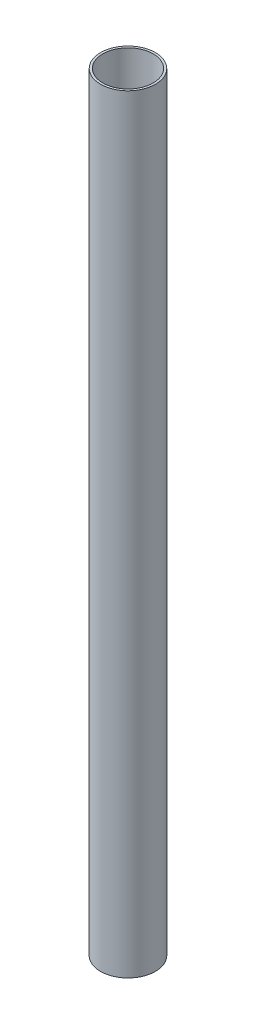
SolidWorks part; units mm, degrees
ref_plane "Front Plane" through (0, 0, 0) normal (0, 0, 1) x (1, 0, 0)
ref_plane "Top Plane" through (0, 0, 0) normal (0, 1, 0) x (1, 0, 0)
ref_plane "Right Plane" through (0, 0, 0) normal (1, 0, 0) x (0, 0, -1)
sketch "Sketch1" plane through (0, 0, 0) normal (0, 1, 0) x (1, 0, 0)
  circle A0 centre (0, 0) radius 12.5
  circle A1 centre (0, 0) radius 11.5
  dimension "D1" = 25
  dimension "D2" = 23
extrude "Boss-Extrude1" add sketch "Sketch1" along normal blind 350
